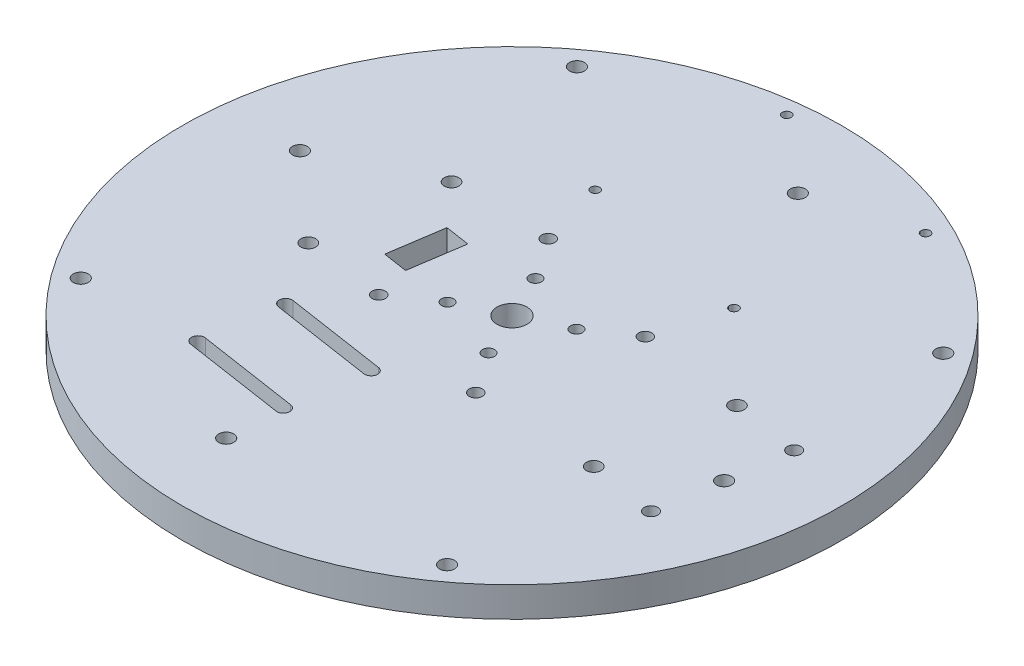
SolidWorks part; units mm, degrees
material "Aleación 6061"
ref_plane "Alzado" through (0, 0, 0) normal (0, 0, 1) x (1, 0, 0)
ref_plane "Planta" through (0, 0, 0) normal (0, 1, 0) x (1, 0, 0)
ref_plane "Vista lateral" through (0, 0, 0) normal (1, 0, 0) x (0, 0, -1)
sketch "Croquis1" plane through (0, 0, 0) normal (0, 1, 0) x (1, 0, 0)
  circle A0 centre (0, 0) radius 110
  dimension "D1" = 220
extrude "Saliente-Extruir1" add sketch "Croquis1" along normal blind 10
sketch "Croquis2" plane through (0, 10, 0) normal (0, 1, 0) x (1, 0, 0)
  line L0 (-11.481, -64.816) -> (-45.0978, -59.7252) construction
  line L3 (-41.2475, -34.285) -> (-7.6303, -39.3728) construction
  line L4 (-40.9257, -32.1592) -> (-7.3086, -37.247)
  line L5 (-41.5692, -36.4107) -> (-7.952, -41.4986)
  line L6 (-11.803, -66.9417) -> (-45.4197, -61.851)
  line L7 (-11.1591, -62.6902) -> (-44.7759, -57.5995)
  arc A2 (-40.9257, -32.1592) -> (-41.5692, -36.4107) centre (-41.2475, -34.285) ccw
  arc A3 (-7.952, -41.4986) -> (-7.3086, -37.247) centre (-7.6303, -39.3728) ccw
  arc A4 (-11.803, -66.9417) -> (-11.1591, -62.6902) centre (-11.481, -64.816) ccw
  arc A5 (-44.7759, -57.5995) -> (-45.4197, -61.851) centre (-45.0978, -59.7252) ccw
  point P4 (-28.2894, -62.2706)
  point P11 (-24.4389, -36.8289)
  dimension "D1" = 2.15
  dimension "D2" = 2.15
extrude "Cortar-Extruir1" cut sketch "Croquis2" against normal blind 10
sketch "Croquis4" plane through (0, 0, 0) normal (0, -1, 0) x (1, 0, 0)
  circle A0 centre (-6.8508, -14.6735) radius 2
  circle A2 centre (14.6735, -6.8508) radius 2
  circle A3 centre (-14.6735, 6.8508) radius 2
  circle A4 centre (6.8508, 14.6735) radius 2
extrude "Cortar-Extruir3" cut sketch "Croquis4" against normal through all
sketch "Croquis5" plane through (0, 10, 0) normal (0, 1, 0) x (1, 0, 0)
  circle A0 centre (-48.762, 28.5802) radius 2.45
  circle A1 centre (-55.047, -12.9469) radius 2.45
  circle A2 centre (63.492, 11.5909) radius 2.45
  circle A4 centre (57.207, -29.9362) radius 2.45
  circle A5 centre (85.9946, 8.1852) radius 2.25
  circle A6 centre (79.7096, -33.3419) radius 2.25
extrude "Cortar-Extruir4" cut sketch "Croquis5" against normal blind 7
sketch "Croquis8" plane through (0, 10, 0) normal (0, 1, 0) x (1, 0, 0)
  circle A0 centre (0, 0) radius 5
extrude "Cortar-Extruir5" cut sketch "Croquis8" against normal through all
sketch "Croquis11" plane through (0, 0, 0) normal (0, -1, 0) x (1, 0, 0)
  circle A0 centre (-83.0942, -12.3027) radius 2.5
  circle A1 centre (12.3027, -83.0942) radius 2.5
  circle A2 centre (83.0942, 12.3027) radius 2.5
  circle A3 centre (-12.3027, 83.0942) radius 2.5
extrude "Cortar-Extruir6" cut sketch "Croquis11" against normal blind 10
sketch "Croquis12" plane through (0, 10, 0) normal (0, 1, 0) x (1, 0, 0)
  circle A1 centre (34.8608, 39.2414) radius 1.5
  circle A2 centre (45.1709, 92.8693) radius 1.5
  circle A3 centre (-12.1985, 103.8987) radius 1.5
  circle A4 centre (-22.5086, 50.2707) radius 1.5
extrude "Cortar-Extruir7" cut sketch "Croquis12" against normal blind 10
sketch "Croquis13" plane through (0, 10, 0) normal (0, 1, 0) x (1, 0, 0)
  line L5 (-39.037, -3.446) -> (-30.8356, -4.6872)
  line L14 (-30.8356, -4.6872) -> (-28.1046, 13.358)
  line L15 (-28.1046, 13.358) -> (-36.3059, 14.5993)
  line L16 (-36.3059, 14.5993) -> (-39.037, -3.446)
extrude "Cortar-Extruir8" cut sketch "Croquis13" against normal through all
sketch "Croquis14" plane through (0, 10, 0) normal (0, 1, 0) x (1, 0, 0)
  circle A1 centre (-61.1283, 82.8108) radius 2.5
  circle A2 centre (-82.8108, -61.1283) radius 2.5
  circle A3 centre (61.1283, -82.8108) radius 2.5
  circle A4 centre (82.8108, 61.1283) radius 2.5
extrude "Cortar-Extruir9" cut sketch "Croquis14" against normal blind 5
sketch "Croquis17" plane through (0, 0, 0) normal (0, -1, 0) x (1, 0, 0)
  circle A4 centre (-28.2909, 16.2026) radius 2.1865
  circle A5 centre (16.2026, 28.2909) radius 2.1865
  circle A6 centre (28.2909, -16.2026) radius 2.1865
  circle A8 centre (-16.2026, -28.2909) radius 2.1865
extrude "Cortar-Extruir10" cut sketch "Croquis17" against normal through all
